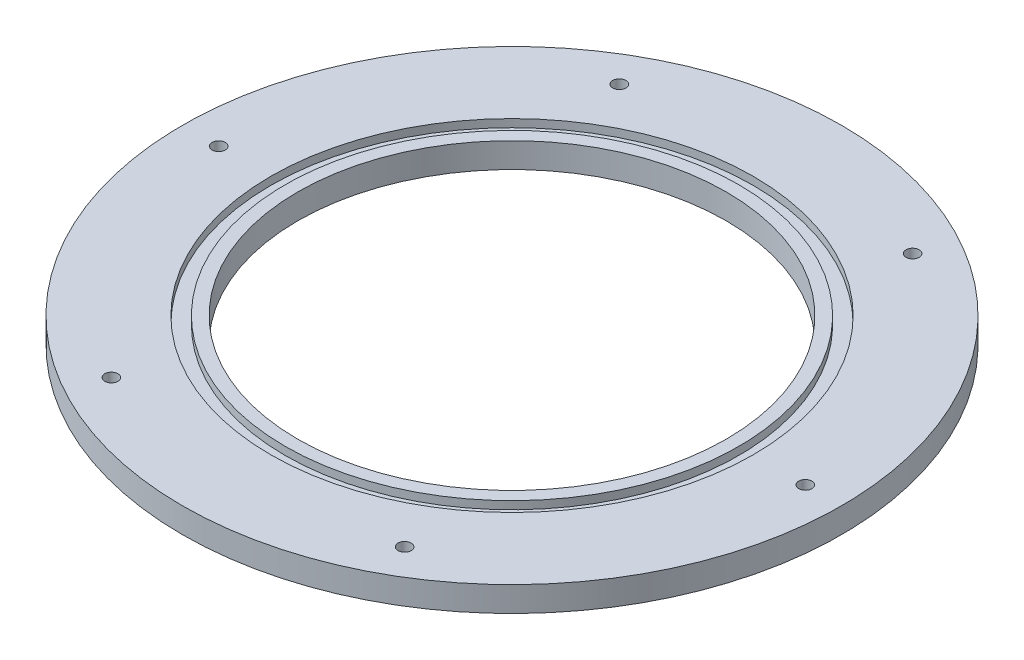
SolidWorks part; units mm, degrees
material "Pine"
ref_plane "Front Plane" through (0, 0, 0) normal (0, 0, 1) x (1, 0, 0)
ref_plane "Top Plane" through (0, 0, 0) normal (0, 1, 0) x (1, 0, 0)
ref_plane "Right Plane" through (0, 0, 0) normal (1, 0, 0) x (0, 0, -1)
sketch "Sketch1" plane through (0, 0, 0) normal (0, 1, 0) x (1, 0, 0)
  circle A0 centre (0, 0) radius 250
  circle A1 centre (0, 0) radius 162.5
  dimension "D1" = 500
  dimension "D2" = 325
extrude "Boss-Extrude1" add sketch "Sketch1" along normal mid plane 19
sketch "Sketch2" plane through (0, 9.5, 0) normal (0, 1, 0) x (1, 0, 0)
  line L0 (0, -1000) -> (0, 49000) construction
  line L1 (-1000, 0) -> (49000, 0) construction
  line L2 (-500, -866.0254) -> (24500, 42435.2448) construction
  line L3 (-500, 866.0254) -> (24500, -42435.2448) construction
  circle A0 centre (111.25, 192.6907) radius 5
  circle A1 centre (222.5, 0) radius 5
  circle A2 centre (-222.5, 0) radius 5
  circle A3 centre (-111.25, 192.6907) radius 5
  circle A4 centre (111.25, -192.6907) radius 5
  circle A5 centre (-111.25, -192.6907) radius 5
  dimension "D1" = 222.5
  dimension "D2" = 10
  dimension "D3" = 10
  dimension "D4" = 222.5
extrude "Cut-Extrude1" cut sketch "Sketch2" against normal through all
sketch "Sketch3" plane through (0, 9.5, 0) normal (0, 1, 0) x (1, 0, 0)
  circle A0 centre (0, 0) radius 172
  circle A1 centre (0, 0) radius 183
  circle A2 centre (0, 0) radius 162.5 construction
  dimension "D1" = 9.5
  dimension "D2" = 11
extrude "Cut-Extrude2" cut sketch "Sketch3" against normal blind 6
